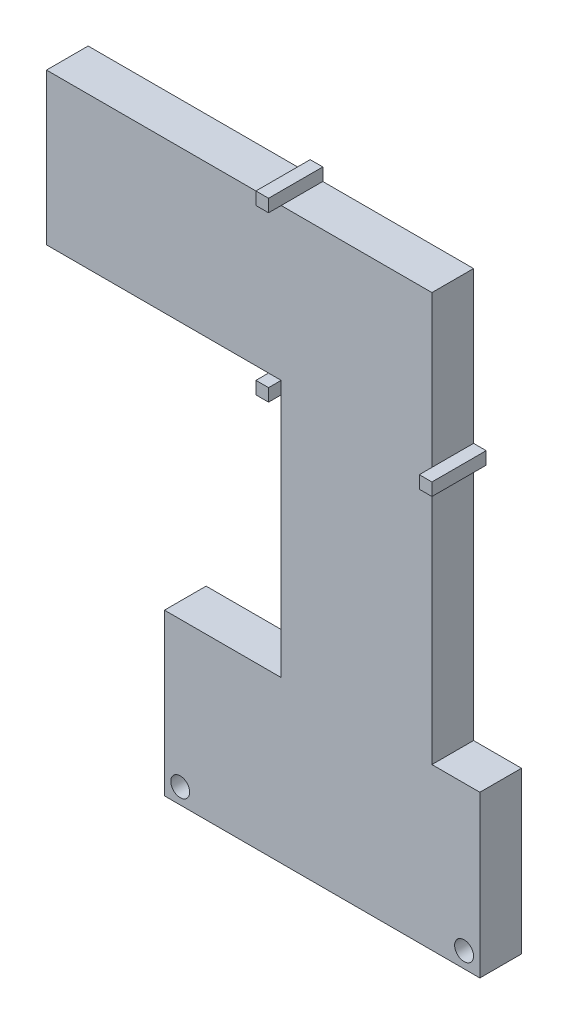
SolidWorks part; units mm, degrees
ref_plane "Ön Düzlem" through (0, 0, 0) normal (1, 0, 0) x (0, 1, 0)
ref_plane "Üst Düzlem" through (0, 0, 0) normal (0, 0, 1) x (0, 1, 0)
ref_plane "Sağ Düzlem" through (0, 0, 0) normal (0, 1, 0) x (-1, 0, 0)
sketch "Çizim1" plane through (0, 0, 0) normal (0, 0, 1) x (0, 1, 0)
  line L0 (0, 0) -> (171.5, 0)
  line L1 (0, 0) -> (0, 103)
  line L2 (0, 103) -> (63.3, 103)
  line L3 (171.5, 103) -> (171.5, 0)
  line L4 (25.5, 0) -> (25.5, 50)
  line L5 (0, 50) -> (25.5, 50)
  line L6 (63.3, 88.6603) -> (63.3, 68.7)
  line L7 (90.3, 68.7) -> (66.3, 68.7)
  line L8 (90.3, 68.7) -> (90.3, -932.3226) construction
  line L9 (17.5478, 31.5) -> (127.8031, 31.5) construction
  line L10 (17.5478, 7.6) -> (101.9694, 7.6) construction
  line L12 (17.5478, 31.5) -> (17.5478, 7.6) construction
  line L13 (25.5, 31.5) -> (66.3, 31.5)
  line L14 (66.3, 31.5) -> (66.3, 68.7)
  line L16 (90.3, 68.7) -> (90.3, 7.6)
  line L17 (90.3, 7.6) -> (25.5, 7.6)
  line L19 (63.3, 88.6603) -> (63.3, 103)
  line L20 (93.3, 103) -> (93.3, 88.6603)
  line L22 (93.3, 103) -> (171.5, 103)
  line L23 (66.3, 68.7) -> (66.3, -938.0123) construction
  line L24 (63.3, 68.7) -> (66.3, 68.7)
  line L25 (93.3, 88.6603) -> (93.3, 68.7)
  line L26 (93.3, 68.7) -> (90.3, 68.7)
  circle A1 centre (2.5, 47.5) radius 1.5
  circle A2 centre (2.5, 2.5) radius 1.5
  dimension "D1" = 66.3
  dimension "D2" = 90.3
  dimension "D3" = 171.5
  dimension "D4" = 7.6
  dimension "D5" = 31.5
  dimension "D6" = 47.5
  dimension "D7" = 103
  dimension "D8" = 63.3
  dimension "D9" = 68.7
  dimension "D10" = 88.6603
extrude "Yükseklik-Ekstrüzyon1" add sketch "Çizim1" along normal blind 6.6
sketch "Çizim3" plane through (0, 0, 0) normal (0, 0, 1) x (0, 1, 0)
  line L0 (66.3, 31.5) -> (66.3, 33.5)
  line L1 (66.3, 31.5) -> (66.3, 68.7) construction
  line L2 (66.3, 33.5) -> (64.3, 33.5)
  line L3 (64.3, 33.5) -> (64.3, 31.5)
  line L4 (25.5, 31.5) -> (66.3, 31.5) construction
  line L5 (64.3, 31.5) -> (66.3, 31.5)
  line L6 (90.3, 33.5) -> (92.3, 33.5)
  line L7 (90.3, 68.7) -> (90.3, 7.6) construction
  line L8 (92.3, 33.5) -> (92.3, 31.5)
  line L9 (92.3, 31.5) -> (90.3, 31.5)
  line L10 (90.3, 31.5) -> (90.3, 33.5)
  line L11 (64.3, 7.6) -> (64.3, 5.6)
  line L12 (90.3, 7.6) -> (25.5, 7.6) construction
  line L13 (64.3, 5.6) -> (66.3, 5.6)
  line L14 (66.3, 5.6) -> (66.3, 7.6)
  line L15 (64.3, 7.6) -> (66.3, 7.6)
  dimension "D1" = 64.3
extrude "Yükseklik-Ekstrüzyon3" add sketch "Çizim3" along normal up to surface (6.6 mm away) up to face at (-1, 2.5, 6.6)
sketch "Çizim4" plane through (0, 0, 6.6) normal (0, 0, 1) x (1, 0, 0)
  line L0 (-33.5, 92.3) -> (-33.5, 90.3)
  line L1 (-33.5, 90.3) -> (-31.5, 90.3)
  line L2 (-31.5, 90.3) -> (-31.5, 92.3)
  line L3 (-31.5, 92.3) -> (-33.5, 92.3)
  line L4 (-33.5, 66.3) -> (-33.5, 64.3)
  line L5 (-33.5, 66.3) -> (-33.5, 64.3) construction
  line L6 (-33.5, 66.3) -> (-68.7, 66.3) construction
  line L7 (-33.5, 64.3) -> (-31.5, 64.3)
  line L8 (-31.5, 64.3) -> (-31.5, 66.3)
  line L9 (-31.5, 66.3) -> (-33.5, 66.3)
  line L10 (-5.6, 66.3) -> (-5.6, 64.3)
  line L11 (-5.6, 64.3) -> (-7.6, 64.3)
  line L12 (-7.6, 64.3) -> (-7.6, 66.3)
  line L13 (-7.6, 66.3) -> (-5.6, 66.3)
extrude "Yükseklik-Ekstrüzyon4" add sketch "Çizim4" along normal blind 2
